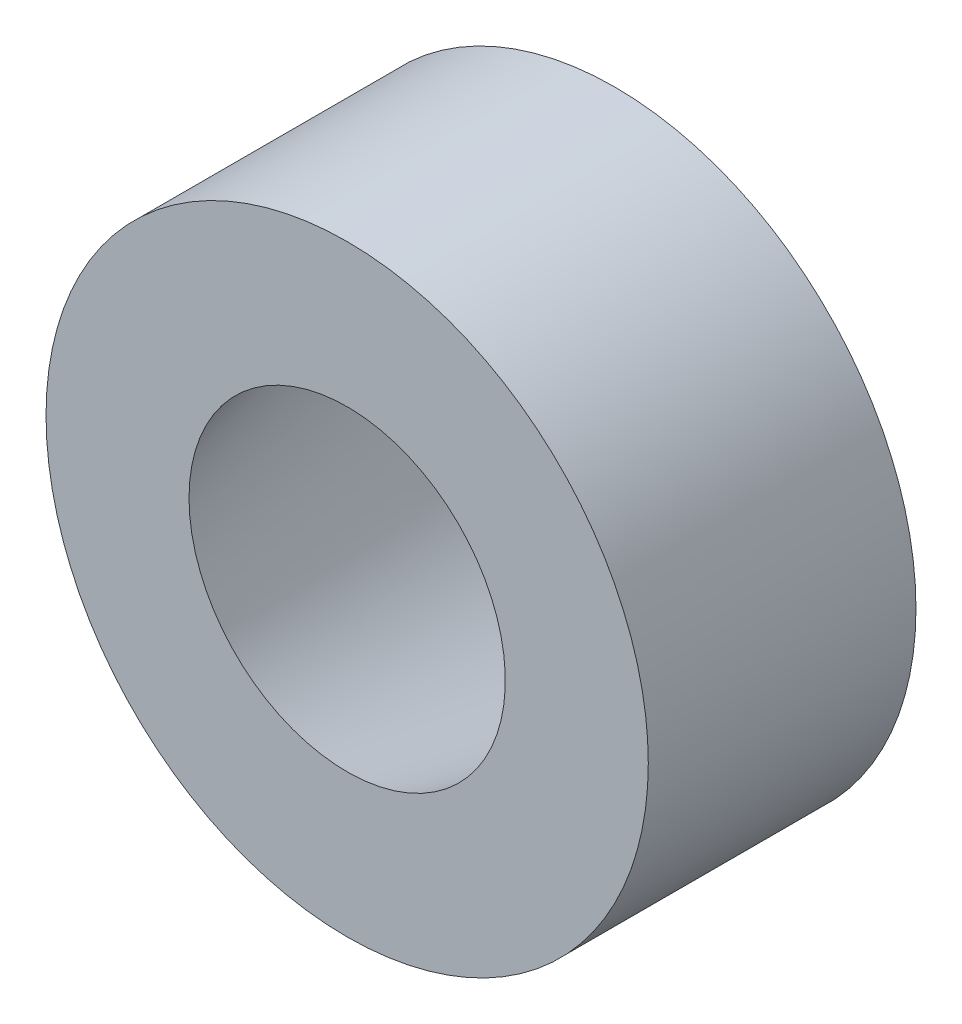
SolidWorks part; units mm, degrees
ref_plane "Face" through (0, 0, 0) normal (0, 0, 1) x (1, 0, 0)
ref_plane "Dessus" through (0, 0, 0) normal (0, 1, 0) x (1, 0, 0)
ref_plane "Droite" through (0, 0, 0) normal (1, 0, 0) x (0, 0, -1)
sketch "Esquisse1" plane through (0, 0, 0) normal (0, 0, 1) x (1, 0, 0)
  circle A0 centre (0, 0) radius 9
  dimension "D1" = 18
extrude "Base-Extrusion" add sketch "Esquisse1" along normal blind 8
sketch "Esquisse2" plane through (0, 0, 0) normal (0, 0, -1) x (-1, 0, 0)
  circle A0 centre (0, 0) radius 6.5
  dimension "D1" = 13
extrude "Enlèv. mat.-Extru.1" cut sketch "Esquisse2" against normal through all draft 12.5
